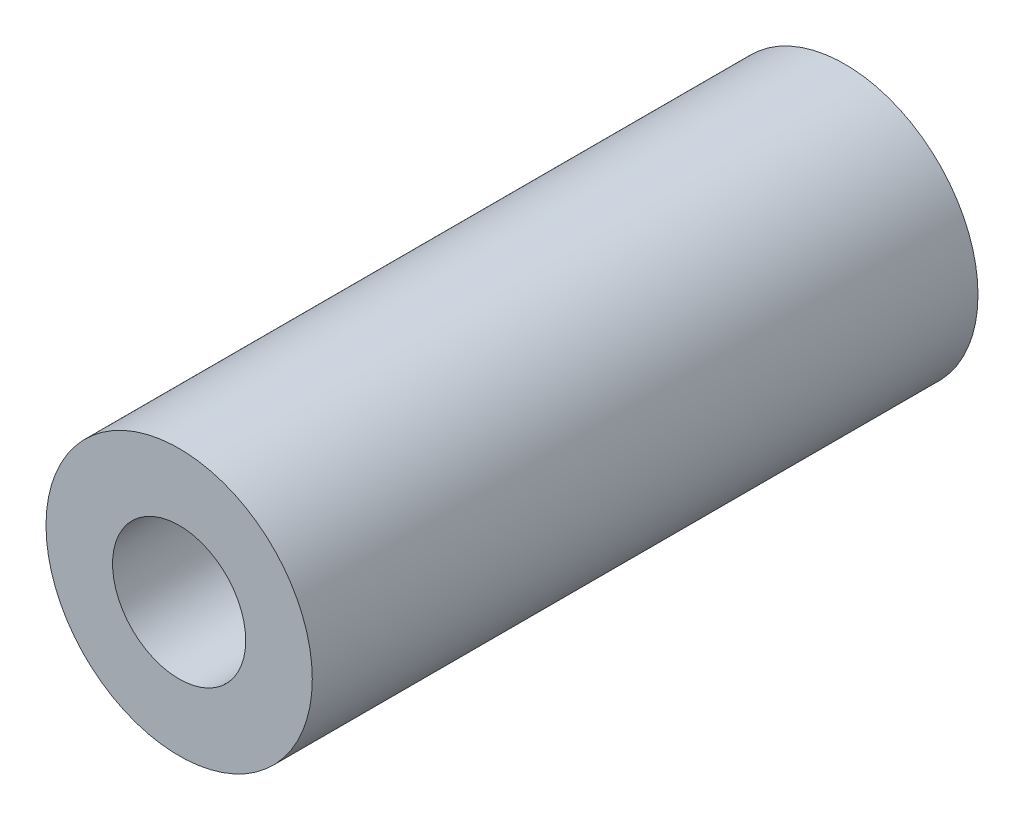
SolidWorks part; units mm, degrees
ref_plane "Front Plane" through (0, 0, 0) normal (0, 0, 1) x (1, 0, 0)
ref_plane "Top Plane" through (0, 0, 0) normal (0, 1, 0) x (1, 0, 0)
ref_plane "Right Plane" through (0, 0, 0) normal (1, 0, 0) x (0, 0, -1)
sketch "Sketch1" plane through (0, 0, 0) normal (0, 0, 1) x (1, 0, 0)
  circle A0 centre (0, 0) radius 2
  circle A1 centre (0, 0) radius 1
  dimension "D1" = 4
  dimension "D2" = 1
extrude "Boss-Extrude1" add sketch "Sketch1" along normal blind 10
